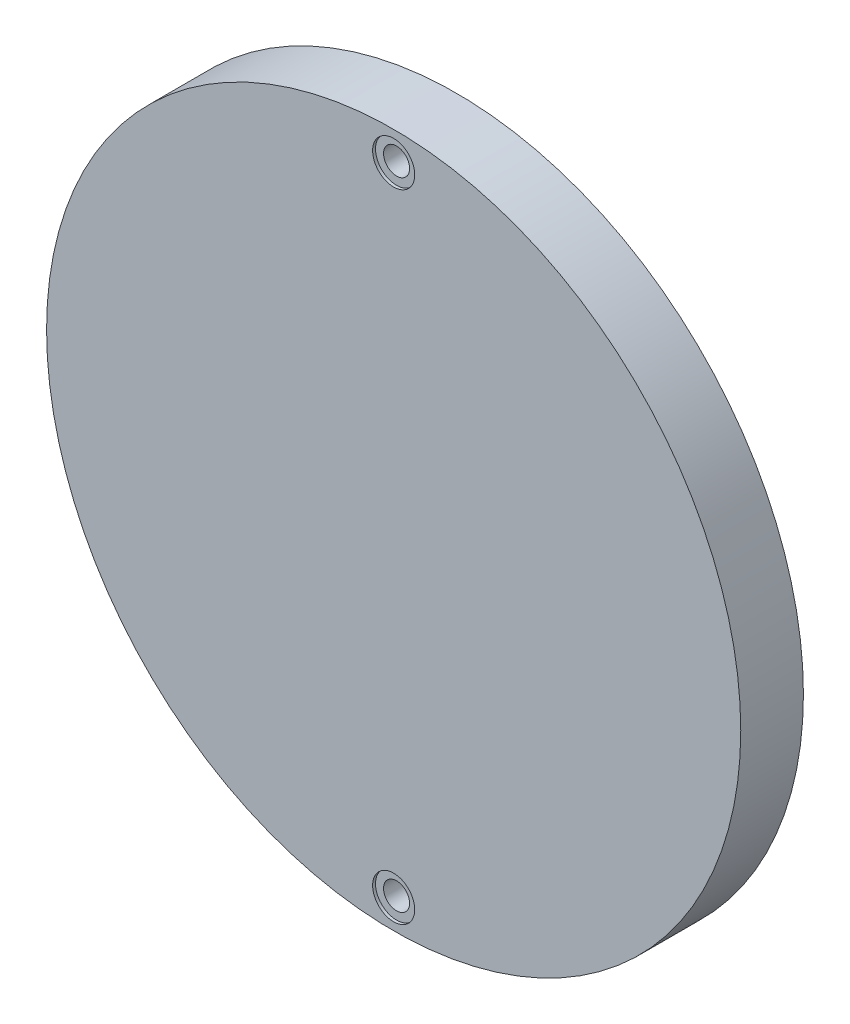
SolidWorks part; units mm, degrees
ref_plane "Front Plane" through (0, 0, 0) normal (0, 0, 1) x (1, 0, 0)
ref_plane "Top Plane" through (0, 0, 0) normal (0, 1, 0) x (1, 0, 0)
ref_plane "Right Plane" through (0, 0, 0) normal (1, 0, 0) x (0, 0, -1)
sketch "Sketch1" plane through (0, 0, 0) normal (0, 0, 1) x (1, 0, 0)
  circle A0 centre (0, 0) radius 36
  dimension "D1" = 72
extrude "Boss-Extrude1" add sketch "Sketch1" along normal blind 6.5
sketch "Sketch2" plane through (0, 0, 0) normal (0, 0, -1) x (-1, 0, 0)
  line L0 (0, 36) -> (0, -36) construction
  line L1 (-36, 0) -> (36, 0) construction
  circle A0 centre (0, 0) radius 36 construction
  circle A1 centre (0, 0) radius 33 construction
  circle A2 centre (0, 33) radius 1.9844
  circle A3 centre (0, -33) radius 1.9844
  dimension "D1" = 66
  dimension "D2" = 3.9688
hole_wizard "#4-40 Tapped Hole1" positions "Sketch9" profile "Sketch10" tap size "#4-40" standard "ANSI Inch"
sketch "Sketch9" plane through (0, 0, 0) normal (0, 0, -1) x (-1, 0, 0)
  point P0 (0, -33)
cosmetic thread "Hole Thread1" parameters "D1"=5.69, "D2"=2.8448
sketch "Sketch10" plane through (0, -33, 0) normal (1, 0, 0) x (0, 1, 0)
  line L0 (0, 0) -> (0, 7.3112)
  line L1 (0, 7.3112) -> (1.35, 6.5)
  line L2 (1.35, 6.5) -> (1.35, 1.1328)
  line L3 (1.35, 1.1328) -> (2.7, 0)
  line L5 (2.7, 0) -> (0, 0)
  line L6 (-1.35, 1.1328) -> (-2.7, 0) construction
  line L10 (0, 7.3112) -> (-1.35, 6.5) construction
  line L11 (0, -6.35) -> (0, 107.95) construction
  dimension "Tap Drill Dia." = 2.7
  dimension "Tap Drill Depth" = 6.5
  dimension "Near C'Sink Dia." = 5.4
  dimension "Near C'Sink Angle" = 100
  dimension "Drill Angle" = 118
sketch "Sketch11" plane through (0, 0, 6.5) normal (0, 0, 1) x (1, 0, 0)
  circle A0 centre (0, -33) radius 2.1844
  dimension "D1" = 4.3688
extrude "Cut-Extrude3" cut sketch "Sketch11" against normal blind 0.3
ref_plane "Plane2" through (0, 0, 0) normal (0, -1, 0) x (-1, 0, 0)
mirror "Mirror1" about plane through (0, 0, 0) normal (0, -1, 0) of "Cut-Extrude3", "#4-40 Tapped Hole1"
